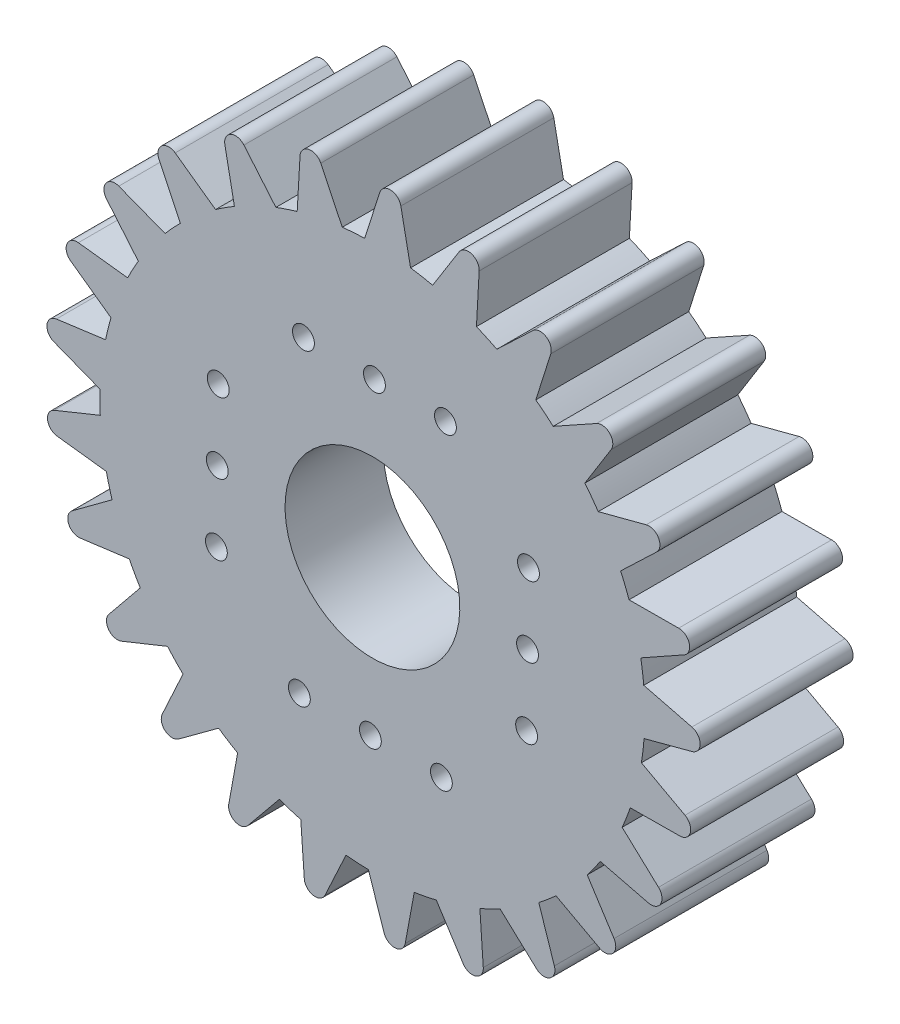
SolidWorks part; units mm, degrees
ref_plane "Front Plane" through (0, 0, 0) normal (0, 0, 1) x (1, 0, 0)
ref_plane "Top Plane" through (0, 0, 0) normal (0, 1, 0) x (1, 0, 0)
ref_plane "Right Plane" through (0, 0, 0) normal (1, 0, 0) x (0, 0, -1)
ref_plane "Plane1" through (0, 0, 74.1) normal (0, 0, -1) x (-1, 0, 0)
sketch "Sketch1" plane through (0, 0, 74.1) normal (0, 0, -1) x (-1, 0, 0)
  line L0 (5.5734, 7.2496) -> (3.9092, 5.7039)
  line L1 (4.3699, 4.8523) -> (6.5743, 5.3991)
  line L2 (7.1726, 4.5637) -> (5.9451, 2.6527)
  line L3 (6.6031, 1.9424) -> (8.6023, 3.0203)
  line L4 (9.3894, 2.3599) -> (8.6758, 0.2037)
  line L5 (9.4897, -0.3207) -> (11.1581, 1.2205)
  line L6 (12.0847, 0.7767) -> (11.9297, -1.4893)
  line L7 (12.8485, -1.7947) -> (14.0811, 0.1129)
  line L8 (15.0891, -0.0865) -> (15.5024, -2.3198)
  line L9 (16.4683, -2.3872) -> (17.1878, -0.2329)
  line L10 (18.2137, -0.1754) -> (19.1695, -2.2358)
  line L11 (20.1218, -2.0609) -> (20.2829, 0.2047)
  line L12 (21.2623, 0.5155) -> (22.7004, -1.2425)
  line L13 (23.5793, -0.8362) -> (23.172, 1.3982)
  line L14 (24.0432, 1.9428) -> (25.8734, 0.5978)
  line L15 (26.6236, 1.2098) -> (25.6734, 3.2728)
  line L16 (26.3819, 4.0169) -> (28.489, 3.1693)
  line L17 (29.0635, 3.9487) -> (27.6301, 5.7105)
  line L18 (28.1312, 6.6075) -> (30.383, 6.3105)
  line L19 (30.7456, 7.2083) -> (28.9191, 8.5583)
  line L20 (29.1814, 9.5517) -> (31.4363, 9.824)
  line L21 (31.5642, 10.7838) -> (29.4593, 11.6371)
  line L22 (29.4663, 12.6646) -> (31.5827, 13.4891)
  line L23 (31.4679, 14.4505) -> (29.2169, 14.7536)
  line L24 (28.9682, 15.7505) -> (30.813, 17.0754)
  line L25 (30.4627, 17.9781) -> (28.2071, 17.7119)
  line L26 (27.7183, 18.6156) -> (29.1756, 20.3577)
  line L27 (28.6119, 21.1449) -> (26.4933, 20.3261)
  line L28 (25.7951, 21.0799) -> (26.7734, 23.1297)
  line L29 (26.0316, 23.7519) -> (24.1832, 22.432)
  line L30 (23.3195, 22.9885) -> (23.7573, 25.2171)
  line L31 (22.8841, 25.6354) -> (21.422, 23.8972)
  line L32 (20.4471, 24.2214) -> (20.3169, 26.4889)
  line L33 (19.367, 26.6769) -> (18.3832, 24.6297)
  line L34 (17.3582, 24.7013) -> (16.6682, 26.8652)
  line L35 (15.7015, 26.811) -> (15.2576, 24.5835)
  line L36 (14.2471, 24.3979) -> (13.0406, 26.3222)
  line L37 (12.1177, 26.0293) -> (12.2418, 23.7614)
  line L38 (11.3091, 23.3303) -> (9.662, 24.8942)
  line L39 (8.841, 24.3809) -> (9.5251, 22.2152)
  line L40 (8.729, 21.5657) -> (6.7447, 22.6708)
  line L41 (6.0771, 21.9695) -> (7.2783, 20.0419)
  line L42 (6.6688, 19.2148) -> (4.472, 19.7917)
  line L43 (3.9997, 18.9464) -> (5.6426, 17.3781)
  line L44 (5.2579, 16.4254) -> (2.9866, 16.4379)
  line L45 (2.7395, 15.5017) -> (4.7208, 14.3913)
  line L46 (4.585, 13.3728) -> (2.382, 12.82)
  line L47 (2.3754, 11.8518) -> (4.5706, 11.269)
  line L48 (4.6924, 10.2488) -> (2.6962, 9.1655)
  line L49 (2.9305, 8.2261) -> (5.2017, 8.2075)
  arc A0 (3.9092, 5.7039) -> (4.3699, 4.8523) centre (4.2495, 5.3376) ccw
  arc A1 (6.5743, 5.3991) -> (7.1726, 4.5637) centre (17.0034, 12.236) ccw
  arc A2 (5.9451, 2.6527) -> (6.6031, 1.9424) centre (6.3658, 2.3825) ccw
  arc A3 (8.6023, 3.0203) -> (9.3894, 2.3599) centre (17.0034, 12.236) ccw
  arc A4 (8.6758, 0.2037) -> (9.4897, -0.3207) centre (9.1504, 0.0466) ccw
  arc A5 (11.1581, 1.2205) -> (12.0847, 0.7767) centre (17.0034, 12.236) ccw
  arc A6 (11.9297, -1.4893) -> (12.8485, -1.7947) centre (12.4285, -1.5234) ccw
  arc A7 (14.0811, 0.1129) -> (15.0891, -0.0865) centre (17.0034, 12.236) ccw
  arc A8 (15.5024, -2.3198) -> (16.4683, -2.3872) centre (15.9941, -2.2288) ccw
  arc A9 (17.1878, -0.2329) -> (18.2137, -0.1754) centre (17.0034, 12.236) ccw
  arc A10 (19.1695, -2.2358) -> (20.1218, -2.0609) centre (19.623, -2.0254) ccw
  arc A11 (20.2829, 0.2047) -> (21.2623, 0.5155) centre (17.0034, 12.236) ccw
  arc A12 (22.7004, -1.2425) -> (23.5793, -0.8362) centre (23.0874, -0.9259) ccw
  arc A13 (23.172, 1.3982) -> (24.0432, 1.9428) centre (17.0034, 12.236) ccw
  arc A14 (25.8734, 0.5978) -> (26.6236, 1.2098) centre (26.1695, 1.0007) ccw
  arc A15 (25.6734, 3.2728) -> (26.3819, 4.0169) centre (17.0034, 12.236) ccw
  arc A16 (28.489, 3.1693) -> (29.0635, 3.9487) centre (28.6756, 3.6332) ccw
  arc A17 (27.6301, 5.7105) -> (28.1312, 6.6075) centre (17.0034, 12.236) ccw
  arc A18 (30.383, 6.3105) -> (30.7456, 7.2083) centre (30.4484, 6.8062) ccw
  arc A19 (28.9191, 8.5583) -> (29.1814, 9.5517) centre (17.0034, 12.236) ccw
  arc A20 (31.4363, 9.824) -> (31.5642, 10.7838) centre (31.3763, 10.3204) ccw
  arc A21 (29.4593, 11.6371) -> (29.4663, 12.6646) centre (17.0034, 12.236) ccw
  arc A22 (31.5827, 13.4891) -> (31.4679, 14.4505) centre (31.4011, 13.955) ccw
  arc A23 (29.2169, 14.7536) -> (28.9682, 15.7505) centre (17.0034, 12.236) ccw
  arc A24 (30.813, 17.0754) -> (30.4627, 17.9781) centre (30.5213, 17.4816) ccw
  arc A25 (28.2071, 17.7119) -> (27.7183, 18.6156) centre (17.0034, 12.236) ccw
  arc A26 (29.1756, 20.3577) -> (28.6119, 21.1449) centre (28.7921, 20.6785) ccw
  arc A27 (26.4933, 20.3261) -> (25.7951, 21.0799) centre (17.0034, 12.236) ccw
  arc A28 (26.7734, 23.1297) -> (26.0316, 23.7519) centre (26.3222, 23.345) ccw
  arc A29 (24.1832, 22.432) -> (23.3195, 22.9885) centre (17.0034, 12.236) ccw
  arc A30 (23.7573, 25.2171) -> (22.8841, 25.6354) centre (23.2667, 25.3135) ccw
  arc A31 (21.422, 23.8972) -> (20.4471, 24.2214) centre (17.0034, 12.236) ccw
  arc A32 (20.3169, 26.4889) -> (19.367, 26.6769) centre (19.8177, 26.4603) ccw
  arc A33 (18.3832, 24.6297) -> (17.3582, 24.7013) centre (17.0034, 12.236) ccw
  arc A34 (16.6682, 26.8652) -> (15.7015, 26.811) centre (16.1918, 26.7133) ccw
  arc A35 (15.2576, 24.5835) -> (14.2471, 24.3979) centre (17.0034, 12.236) ccw
  arc A36 (13.0406, 26.3222) -> (12.1177, 26.0293) centre (12.617, 26.0566) ccw
  arc A37 (12.2418, 23.7614) -> (11.3091, 23.3303) centre (17.0034, 12.236) ccw
  arc A38 (9.662, 24.8942) -> (8.841, 24.3809) centre (9.3177, 24.5316) ccw
  arc A39 (9.5251, 22.2152) -> (8.729, 21.5657) centre (17.0034, 12.236) ccw
  arc A40 (6.7447, 22.6708) -> (6.0771, 21.9695) centre (6.5014, 22.2339) ccw
  arc A41 (7.2783, 20.0419) -> (6.6688, 19.2148) centre (17.0034, 12.236) ccw
  arc A42 (4.472, 19.7917) -> (3.9997, 18.9464) centre (4.345, 19.3081) ccw
  arc A43 (5.6426, 17.3781) -> (5.2579, 16.4254) centre (17.0034, 12.236) ccw
  arc A44 (2.9866, 16.4379) -> (2.7395, 15.5017) centre (2.9839, 15.9379) ccw
  arc A45 (4.7208, 14.3913) -> (4.585, 13.3728) centre (17.0034, 12.236) ccw
  arc A46 (2.382, 12.82) -> (2.3754, 11.8518) centre (2.5037, 12.3351) ccw
  arc A47 (4.5706, 11.269) -> (4.6924, 10.2488) centre (17.0034, 12.236) ccw
  arc A48 (2.6962, 9.1655) -> (2.9305, 8.2261) centre (2.9346, 8.726) ccw
  arc A49 (5.2017, 8.2075) -> (5.5734, 7.2496) centre (17.0034, 12.236) ccw
extrude "Boss-Extrude1" add sketch "Sketch1" against normal blind 7
hole_wizard "Hole1" positions "Sketch3" profile "Sketch2" legacy
sketch "Sketch3" plane through (0, 0, 74.1) normal (0, 0, -1) x (-1, 0, 0)
  point P0 (17.0034, 12.236)
sketch "Sketch2" plane through (-17.0034, 12.236, 74.1) normal (1, 0, 0) x (0, 1, 0)
  line L0 (0, 0) -> (0, 7)
  line L1 (0, 7) -> (4, 7)
  line L2 (4, 7) -> (4, 2.5)
  line L3 (4, 2.5) -> (10.25, 2.5)
  line L4 (10.25, 2.5) -> (10.25, 0)
  line L5 (10.25, 0) -> (0, 0)
  line L6 (0, 110) -> (0, -10) construction
  dimension "Diameter" = 8
  dimension "Depth" = 7
  dimension "C-Bore Diameter" = 20.5
  dimension "C-Bore Depth" = 2.5
hole_wizard "Ø1.0 (1) Diameter Hole1" positions "Sketch5" profile "Sketch4" hole size "Ø1.0" standard "ANSI Metric"
sketch "Sketch5" plane through (0, 0, 81.1) normal (0, 0, 1) x (1, 0, 0)
  point P0 (-13.8468, 5.094)
  point P1 (-17.0965, 5.1366)
  point P2 (-20.3462, 5.1792)
  point P3 (-24.1454, 9.0794)
  point P4 (-24.1028, 12.3291)
  point P5 (-24.0602, 15.5788)
  point P6 (-20.16, 19.378)
  point P7 (-16.9103, 19.3354)
  point P8 (-13.6606, 19.2928)
  point P9 (-9.8614, 15.3926)
  point P10 (-9.904, 12.1429)
  point P11 (-9.9466, 8.8932)
sketch "Sketch4" plane through (-13.8468, 5.094, 81.1) normal (1, 0, 0) x (0, -1, 0)
  line L0 (0, 0) -> (0, 7)
  line L1 (0, 7) -> (0.5, 7)
  line L2 (0.5, 7) -> (0.5, 0)
  line L5 (0.5, 0) -> (0, 0)
  line L11 (0, -6.35) -> (0, 107.95) construction
  dimension "Thru Hole Dia." = 1
  dimension "Thru Hole Depth" = 7
